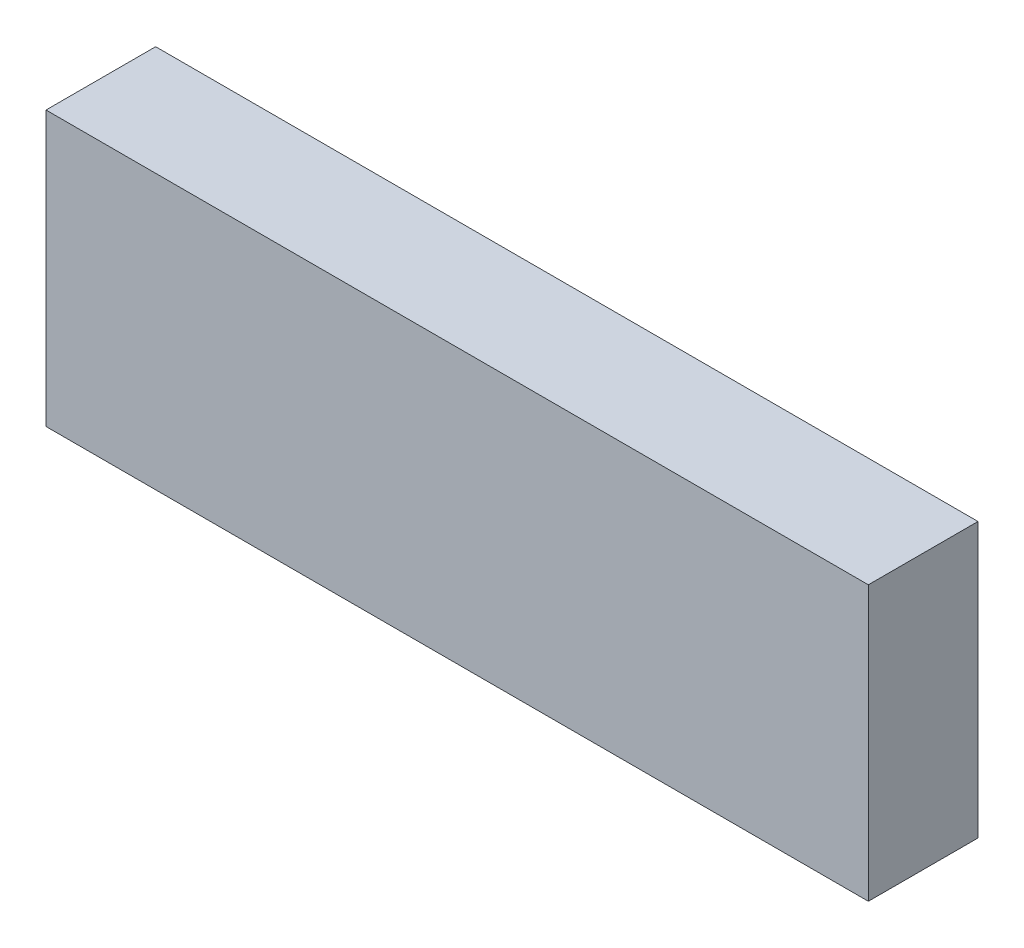
SolidWorks part; units mm, degrees
ref_plane "前视基准面" through (0, 0, 0) normal (0, 0, 1) x (1, 0, 0)
ref_plane "上视基准面" through (0, 0, 0) normal (0, 1, 0) x (1, 0, 0)
ref_plane "右视基准面" through (0, 0, 0) normal (1, 0, 0) x (0, 0, -1)
other "Configuration Table"
sketch "草图1" plane through (0, 0, 0) normal (0, 0, 1) x (1, 0, 0)
  line L1 (-75, -25) -> (75, -25)
  line L2 (-75, -25) -> (-75, 25)
  line L3 (-75, 25) -> (75, 25)
  line L4 (75, -25) -> (75, 25)
  line L5 (-75, -25) -> (75, 25) construction
  line L6 (-75, 25) -> (75, -25) construction
  point P0 (0, 0)
extrude "凸台-拉伸1" add sketch "草图1" along normal blind 20
